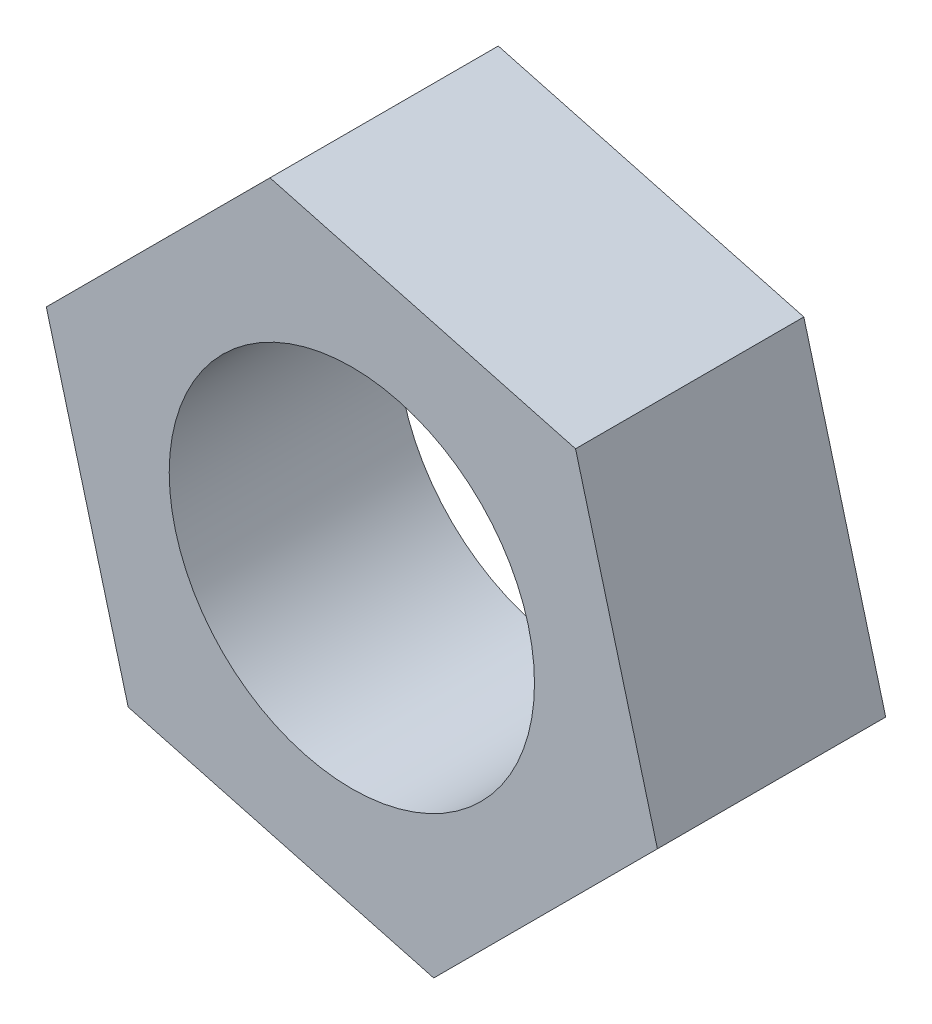
SolidWorks part; units mm, degrees
material "AISI 304"
ref_plane "Alzado" through (0, 0, 0) normal (0, 0, 1) x (1, 0, 0)
ref_plane "Planta" through (0, 0, 0) normal (0, 1, 0) x (1, 0, 0)
ref_plane "Vista lateral" through (0, 0, 0) normal (1, 0, 0) x (0, 0, -1)
sketch "Croquis1" plane through (0, 0, 0) normal (0, 0, 1) x (1, 0, 0)
  circle A0 centre (0, 0) radius 2.5
  circle A1 centre (0, 0) radius 6
extrude "Saliente-Extruir1" add sketch "Croquis1" along normal blind 5
sketch "Croquis2" plane through (0, 0, 5) normal (0, 0, 1) x (1, 0, 0)
  line L8 (-6.6921, 1.7932) -> (-1.7931, 6.6921)
  line L9 (-1.7931, 6.6921) -> (4.899, 4.8989)
  line L10 (4.899, 4.8989) -> (6.6921, -1.7932)
  line L11 (6.6921, -1.7932) -> (1.7931, -6.6921)
  line L12 (1.7931, -6.6921) -> (-4.899, -4.8989)
  line L13 (-4.899, -4.8989) -> (-6.6921, 1.7932)
  circle A3 centre (0, 0) radius 4
  point P13 (0, 0)
  point P15 (-4.2426, 4.2426)
  point P28 (0, 0)
  dimension "D1" = 8
  dimension "D2" = 6
extrude "Saliente-Extruir2" add sketch "Croquis2" against normal blind 5
sketch "Croquis3" plane through (0, 0, 0) normal (0, 0, -1) x (-1, 0, 0)
  circle A0 centre (0, 0) radius 4
extrude "Cortar-Extruir1" cut sketch "Croquis3" against normal blind 10
